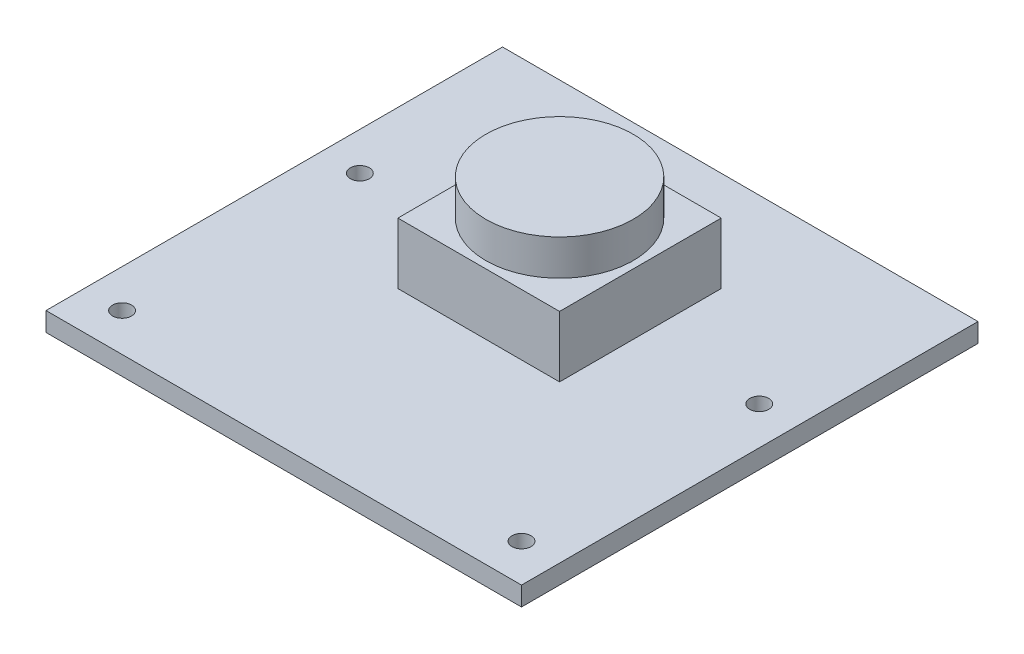
SolidWorks part; units mm, degrees
ref_plane "Front Plane" through (0, 0, 0) normal (0, 0, 1) x (1, 0, 0)
ref_plane "Top Plane" through (0, 0, 0) normal (0, 1, 0) x (1, 0, 0)
ref_plane "Right Plane" through (0, 0, 0) normal (1, 0, 0) x (0, 0, -1)
sketch "Sketch1" plane through (0, 0, 0) normal (0, 1, 0) x (1, 0, 0)
  line L1 (-12.5, -12) -> (12.5, -12)
  line L2 (-12.5, -12) -> (-12.5, 12)
  line L3 (-12.5, 12) -> (12.5, 12)
  line L4 (12.5, -12) -> (12.5, 12)
  line L5 (-12.5, -12) -> (12.5, 12) construction
  line L6 (-12.5, 12) -> (12.5, -12) construction
  point P0 (0, 0)
  dimension "D1" = 25
  dimension "D2" = 24
extrude "Boss-Extrude1" add sketch "Sketch1" along normal blind 1
sketch "Sketch2" plane through (0, 1, 0) normal (0, 1, 0) x (1, 0, 0)
  line L0 (-12.5, -12) -> (12.5, -12) construction
  line L1 (-12.5, 12) -> (-12.5, -12) construction
  line L2 (0, 0) -> (0, -12) construction
  line L3 (0, -12) -> (0, 0) construction
  line L4 (0, 0) -> (12.5, 0) construction
  line L5 (12.5, -12) -> (12.5, 12) construction
  circle A0 centre (-10.5, -10) radius 0.5
  circle A1 centre (10.5, -10) radius 0.5
  circle A4 centre (-10.5, 2.5) radius 0.5
  circle A5 centre (10.5, 2.5) radius 0.5
  point P22 (-12.5, -0.0384)
  point P23 (-10.5164, 2.4999)
  point P24 (0, 0)
  dimension "D1" = 1
  dimension "D4" = 1
  dimension "D2" = 2
  dimension "D3" = 2
  dimension "D5" = 14.5
  dimension "D6" = 2
extrude "Cut-Extrude1" cut sketch "Sketch2" against normal through all
sketch "Sketch3" plane through (0, 1, 0) normal (0, 1, 0) x (1, 0, 0)
  line L0 (-12.5, -12) -> (12.5, -12) construction
  line L1 (-4.25, -1.75) -> (4.25, -1.75)
  line L2 (-4.25, -1.75) -> (-4.25, 6.75)
  line L3 (-4.25, 6.75) -> (4.25, 6.75)
  line L4 (4.25, -1.75) -> (4.25, 6.75)
  line L5 (-4.25, -1.75) -> (4.25, 6.75) construction
  line L6 (-4.25, 6.75) -> (4.25, -1.75) construction
  point P0 (0, 2.5)
  point P7 (0, 0)
  dimension "D1" = 14.5
  dimension "D2" = 8.5
  dimension "D3" = 8.5
extrude "Boss-Extrude2" add sketch "Sketch3" along normal blind 3.21
sketch "Sketch4" plane through (0, 4.21, 0) normal (0, 1, 0) x (1, 0, 0)
  line L0 (4.25, -1.75) -> (4.25, 6.75) construction
  line L1 (-4.25, -1.75) -> (4.25, -1.75) construction
  circle A0 centre (0, 2.5) radius 3.8766
  point P2 (0, 0)
  point P5 (4.25, 2.5)
  point P8 (0, -1.75)
  dimension "D1" = 7.7531
extrude "Boss-Extrude3" add sketch "Sketch4" along normal blind 1.88
ref_plane "Plane1" through (0, 0, 0) normal (-1, 0, 0) x (0, 0, 1)
sketch "Sketch5" plane through (0, 0, 0) normal (-1, 0, 0) x (0, 0, 1)
  line L0 (-2.5, 6.09) -> (-18.9685, 34.6143)
  line L1 (1.3766, 6.09) -> (-6.3766, 6.09) construction
  line L2 (-18.9685, 34.6143) -> (-2.5, 6.09)
  line L3 (-2.5, 6.09) -> (13.9161, 34.5236)
  line L4 (-2.5, 6.09) -> (-2.5, 21.7179) construction
  point P4 (13.0891, 35.0011)
  point P7 (-18.1415, 35.0011)
  dimension "D1" = 30
  dimension "D2" = 30
